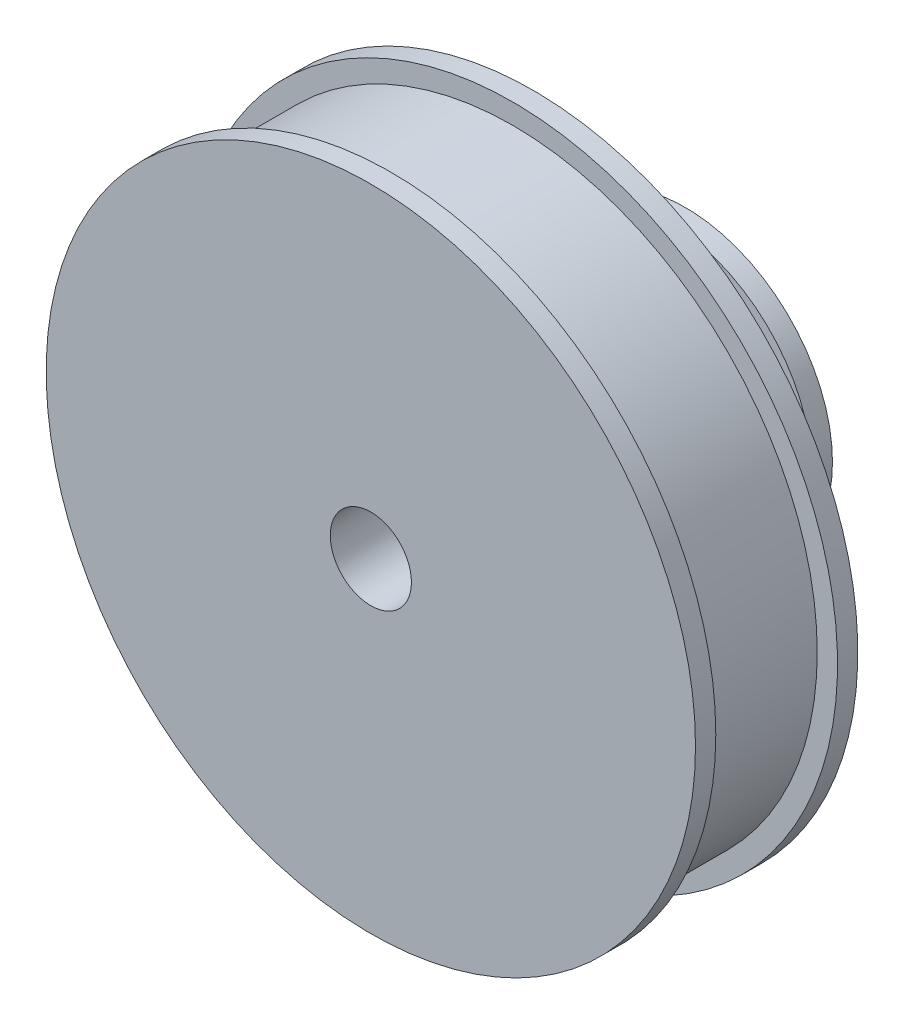
SolidWorks part; units mm, degrees
ref_plane "前视基准面" through (0, 0, 0) normal (0, 0, 1) x (1, 0, 0)
ref_plane "上视基准面" through (0, 0, 0) normal (0, 1, 0) x (1, 0, 0)
ref_plane "右视基准面" through (0, 0, 0) normal (1, 0, 0) x (0, 0, -1)
sketch "草图1" plane through (0, 0, 0) normal (0, 0, 1) x (1, 0, 0)
  circle A0 centre (0, 0) radius 12.5
  dimension "D1" = 25
extrude "拉伸1" add sketch "草图1" along normal blind 15
sketch "草图2" plane through (0, 0, 15) normal (0, 0, 1) x (1, 0, 0)
  circle A0 centre (0, 0) radius 30
  dimension "D1" = 60
extrude "拉伸2" add sketch "草图2" along normal blind 14
sketch "草图3" plane through (0, 0, 29) normal (0, 0, 1) x (1, 0, 0)
  circle A0 centre (0, 0) radius 32
  dimension "D1" = 64
extrude "拉伸3" add sketch "草图3" against normal blind 2
sketch "草图4" plane through (0, 0, 15) normal (0, 0, -1) x (-1, 0, 0)
  circle A0 centre (0, 0) radius 32 construction
  circle A1 centre (0, 0) radius 32
extrude "拉伸4" add sketch "草图4" along normal blind 2
sketch "草图5" plane through (0, 0, 0) normal (0, 0, -1) x (-1, 0, 0)
  circle A0 centre (0, 0) radius 14.5
  dimension "D1" = 29
extrude "拉伸5" add sketch "草图5" along normal blind 2
sketch "草图6" plane through (0, 0, 29) normal (0, 0, 1) x (1, 0, 0)
  circle A0 centre (0, 0) radius 4
  dimension "D1" = 8
extrude "切除-拉伸1" cut sketch "草图6" against normal through all
